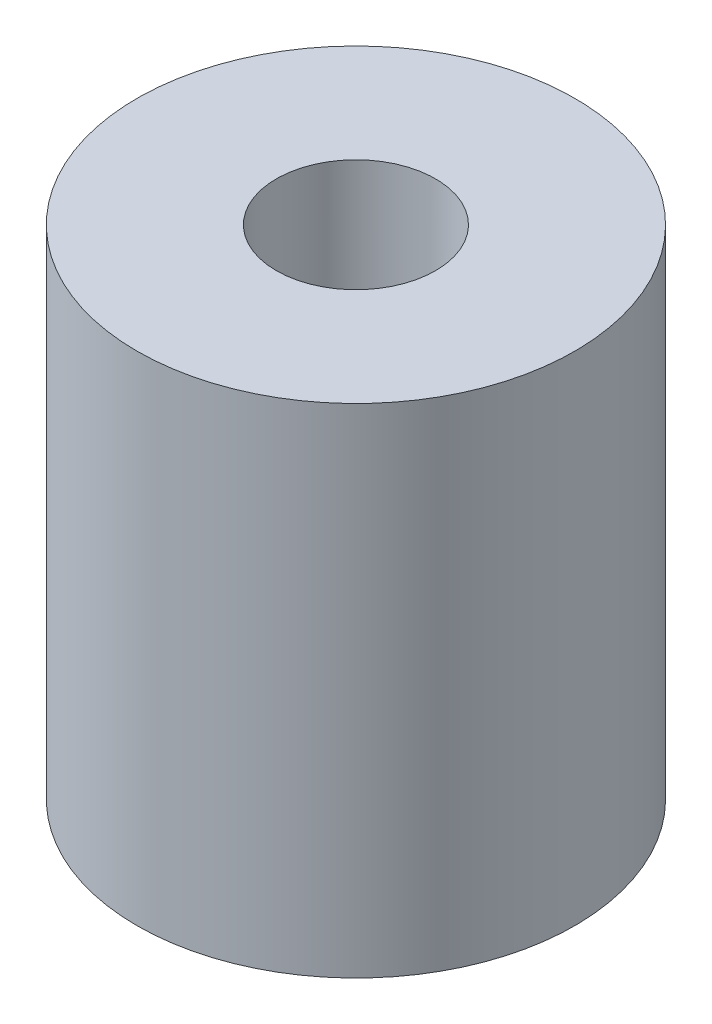
SolidWorks part; units mm, degrees
ref_plane "Front Plane" through (0, 0, 0) normal (0, 0, 1) x (1, 0, 0)
ref_plane "Top Plane" through (0, 0, 0) normal (0, 1, 0) x (1, 0, 0)
ref_plane "Right Plane" through (0, 0, 0) normal (1, 0, 0) x (0, 0, -1)
sketch "Sketch1" plane through (0, 0, 0) normal (0, 1, 0) x (1, 0, 0)
  circle A0 centre (0, 0) radius 11
  dimension "D1" = 22
extrude "Boss-Extrude1" add sketch "Sketch1" along normal blind 25
sketch "Sketch2" plane through (0, 25, 0) normal (0, 1, 0) x (1, 0, 0)
  circle A0 centre (0, 0) radius 4
  dimension "D1" = 8
extrude "Cut-Extrude1" cut sketch "Sketch2" against normal through all
sketch "Sketch3" plane through (0, 0, 0) normal (0, -1, 0) x (1, 0, 0)
  line L0 (4.8645, 3.521) -> (6.5054, 5.1619)
  line L2 (0.95, 5.9294) -> (0.95, 8.25)
  line L3 (0.95, 8.25) -> (-0.95, 8.25)
  line L4 (-0.95, 5.9294) -> (-0.95, 8.25)
  line L5 (0, 6.005) -> (-0.95, 8.25) construction
  line L6 (0.95, 8.25) -> (0, 6.005) construction
  line L7 (6.5054, 5.1619) -> (5.1619, 6.5054)
  line L8 (3.521, 4.8645) -> (5.1619, 6.5054)
  line L9 (4.2462, 4.2462) -> (5.1619, 6.5054) construction
  line L10 (6.5054, 5.1619) -> (4.2462, 4.2462) construction
  line L11 (5.9294, -0.95) -> (8.25, -0.95)
  line L12 (8.25, -0.95) -> (8.25, 0.95)
  line L13 (5.9294, 0.95) -> (8.25, 0.95)
  line L14 (6.005, 0) -> (8.25, 0.95) construction
  line L15 (8.25, -0.95) -> (6.005, 0) construction
  line L16 (3.521, -4.8645) -> (5.1619, -6.5054)
  line L17 (5.1619, -6.5054) -> (6.5054, -5.1619)
  line L18 (4.8645, -3.521) -> (6.5054, -5.1619)
  line L19 (4.2462, -4.2462) -> (6.5054, -5.1619) construction
  line L20 (5.1619, -6.5054) -> (4.2462, -4.2462) construction
  line L21 (-0.95, -5.9294) -> (-0.95, -8.25)
  line L22 (-0.95, -8.25) -> (0.95, -8.25)
  line L23 (0.95, -5.9294) -> (0.95, -8.25)
  line L24 (0, -6.005) -> (0.95, -8.25) construction
  line L25 (-0.95, -8.25) -> (0, -6.005) construction
  line L26 (-4.8645, -3.521) -> (-6.5054, -5.1619)
  line L27 (-6.5054, -5.1619) -> (-5.1619, -6.5054)
  line L28 (-3.521, -4.8645) -> (-5.1619, -6.5054)
  line L29 (-4.2462, -4.2462) -> (-5.1619, -6.5054) construction
  line L30 (-6.5054, -5.1619) -> (-4.2462, -4.2462) construction
  line L31 (-5.9294, 0.95) -> (-8.25, 0.95)
  line L32 (-8.25, 0.95) -> (-8.25, -0.95)
  line L33 (-5.9294, -0.95) -> (-8.25, -0.95)
  line L34 (-6.005, 0) -> (-8.25, -0.95) construction
  line L35 (-8.25, 0.95) -> (-6.005, 0) construction
  line L36 (-3.521, 4.8645) -> (-5.1619, 6.5054)
  line L37 (-5.1619, 6.5054) -> (-6.5054, 5.1619)
  line L38 (-4.8645, 3.521) -> (-6.5054, 5.1619)
  line L39 (-4.2462, 4.2462) -> (-6.5054, 5.1619) construction
  line L40 (-5.1619, 6.5054) -> (-4.2462, 4.2462) construction
  arc A0 (-4.8645, 3.521) -> (-5.9294, 0.95) centre (0, 0) ccw
  arc A1 (-5.9294, -0.95) -> (-4.8645, -3.521) centre (0, 0) ccw
  arc A2 (-3.521, -4.8645) -> (-0.95, -5.9294) centre (0, 0) ccw
  arc A3 (0.95, -5.9294) -> (3.521, -4.8645) centre (0, 0) ccw
  arc A4 (-0.95, 5.9294) -> (-3.521, 4.8645) centre (0, 0) ccw
  arc A5 (3.521, 4.8645) -> (0.95, 5.9294) centre (0, 0) ccw
  arc A6 (5.9294, 0.95) -> (4.8645, 3.521) centre (0, 0) ccw
  arc A7 (4.8645, -3.521) -> (5.9294, -0.95) centre (0, 0) ccw
  point P3 (0, 6.005)
  point P17 (0, 8.25)
  dimension "D1" = 12.01
  dimension "D2" = 1.9
  dimension "D3" = 8
  dimension "D4" = 8.25
extrude "Cut-Extrude2" cut sketch "Sketch3" against normal blind 7.5
sketch "Sketch4" plane through (0, 0, 0) normal (0, 0, 1) x (1, 0, 0)
  line L0 (11, 25) -> (-11, 25) construction
  circle A0 centre (0, 19) radius 1.5
  dimension "D1" = 3
  dimension "D2" = 6
extrude "Cut-Extrude3" cut sketch "Sketch4" against normal through all
sketch "Sketch5" plane through (0, 0, 0) normal (1, 0, 0) x (0, 0, -1)
  line L0 (11, 25) -> (-11, 25) construction
  circle A0 centre (0, 19) radius 1.5
  dimension "D1" = 3
  dimension "D2" = 6
extrude "Cut-Extrude4" cut sketch "Sketch5" against normal through all
sketch "Sketch7" plane through (0, 0, 0) normal (0, 0, 1) x (1, 0, 0)
  circle A0 centre (0, 19) radius 2.1
  dimension "D1" = 4.2
extrude "Cut-Extrude5" cut sketch "Sketch7" against normal blind 10 from offset 10.2 offset against normal yes
sketch "Sketch8" plane through (0, 0, 0) normal (1, 0, 0) x (0, 0, -1)
  circle A0 centre (0, 19) radius 2.1
  dimension "D1" = 4.2
extrude "Cut-Extrude6" cut sketch "Sketch8" against normal blind 10 from offset 10.2
